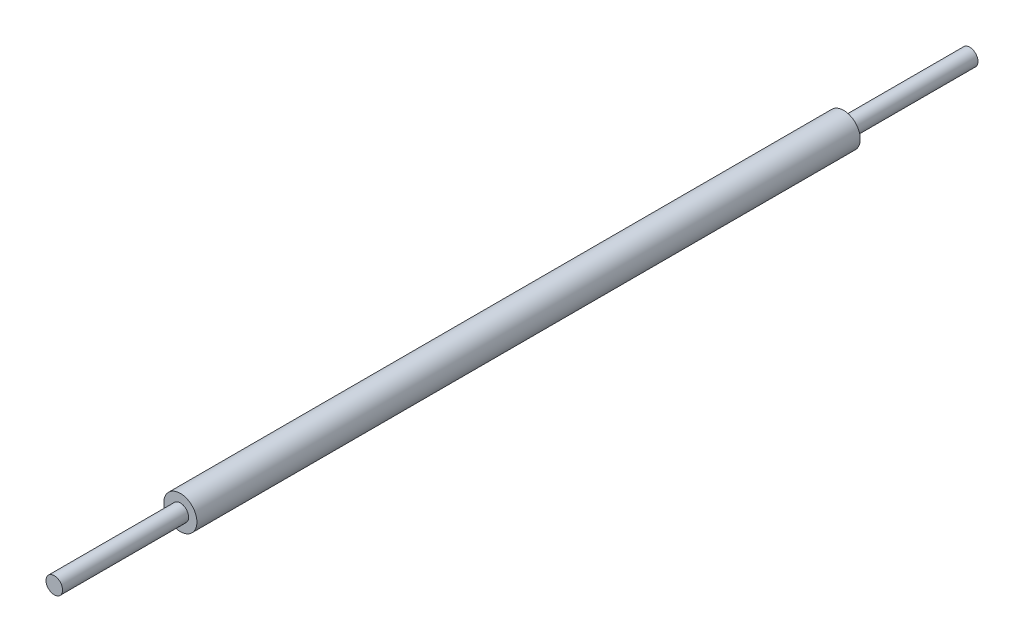
SolidWorks part; units mm, degrees
ref_plane "Front Plane" through (0, 0, 0) normal (0, 0, 1) x (1, 0, 0)
ref_plane "Top Plane" through (0, 0, 0) normal (0, 1, 0) x (1, 0, 0)
ref_plane "Right Plane" through (0, 0, 0) normal (1, 0, 0) x (0, 0, -1)
sketch "Sketch2" plane through (0, 0, 0) normal (0, 0, 1) x (1, 0, 0)
  circle A0 centre (0, 0) radius 6.35
  dimension "D1" = 12.7
extrude "Boss-Extrude2" add sketch "Sketch2" along normal blind 96.52
sketch "Sketch7" plane through (0, 0, 96.52) normal (0, 0, 1) x (1, 0, 0)
  circle A0 centre (0, 0) radius 12.7
  dimension "D1" = 25.4
extrude "Boss-Extrude3" add sketch "Sketch7" along normal blind 508
sketch "Sketch11" plane through (0, 0, 604.52) normal (0, 0, 1) x (1, 0, 0)
  circle A0 centre (0, 0) radius 12.7
  dimension "D1" = 25.4
sketch "Sketch13" plane through (0, 0, 604.52) normal (0, 0, 1) x (1, 0, 0)
  circle A0 centre (0, 0) radius 6.35
  dimension "D1" = 12.7
extrude "Boss-Extrude4" add sketch "Sketch13" along normal blind 96.52
